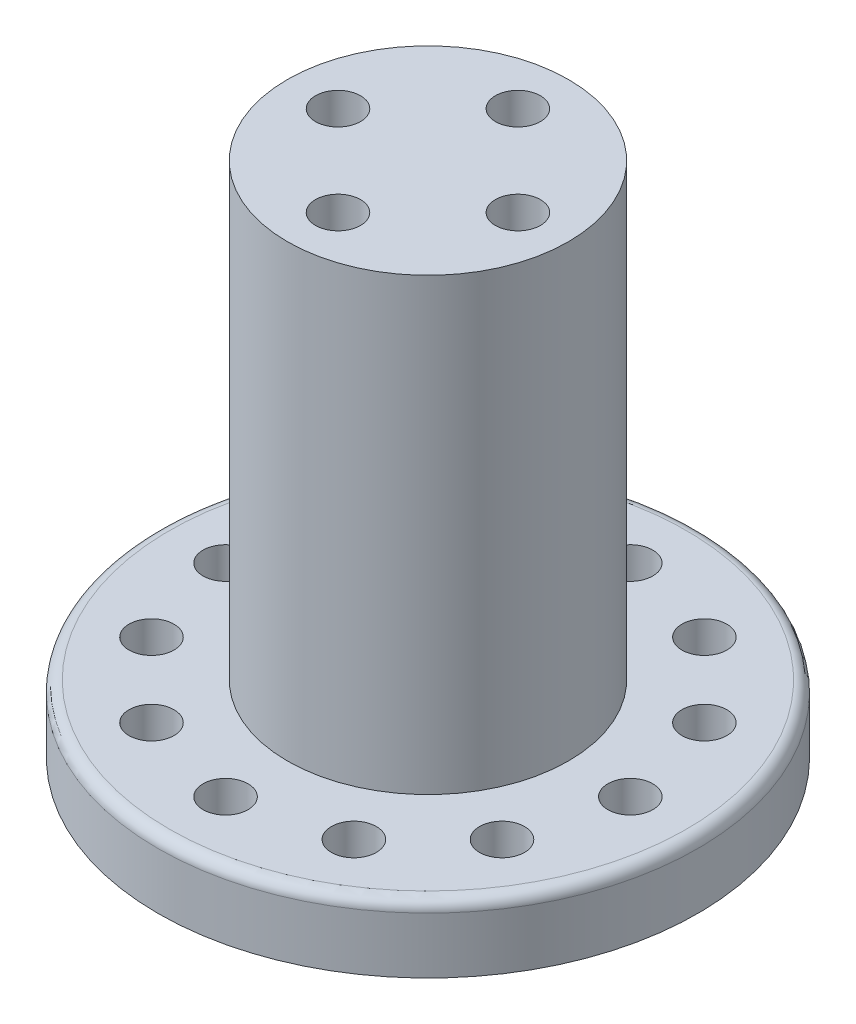
SolidWorks part; units mm, degrees
ref_plane "Front Plane" through (0, 0, 0) normal (0, 0, 1) x (1, 0, 0)
ref_plane "Top Plane" through (0, 0, 0) normal (0, 1, 0) x (1, 0, 0)
ref_plane "Right Plane" through (0, 0, 0) normal (1, 0, 0) x (0, 0, -1)
sketch "Sketch1" plane through (0, 0, 0) normal (0, 1, 0) x (1, 0, 0)
  line L0 (0, 0) -> (-22595.0444, 0) construction
  line L1 (0, 0) -> (0, -22595.0444) construction
  circle A0 centre (0, 0) radius 24
  dimension "D1" = 48
extrude "Boss-Extrude1" add sketch "Sketch1" along normal blind 6
sketch "Sketch2" plane through (0, 6, 0) normal (0, 1, 0) x (1, 0, 0)
  line L0 (0, 0) -> (-50000, 0) construction
  line L1 (0, 0) -> (0, -50000) construction
  circle A0 centre (0, 0) radius 18 construction
  circle A1 centre (0, 18) radius 2
  circle A2 centre (9, 15.5885) radius 2
  circle A3 centre (15.5885, 9) radius 2
  circle A4 centre (18, 0) radius 2
  circle A5 centre (15.5885, -9) radius 2
  circle A6 centre (9, -15.5885) radius 2
  circle A7 centre (0, -18) radius 2
  circle A8 centre (-9, -15.5885) radius 2
  circle A9 centre (-15.5885, -9) radius 2
  circle A10 centre (-18, 0) radius 2
  circle A11 centre (-15.5885, 9) radius 2
  circle A12 centre (-9, 15.5885) radius 2
  point P34 (0, 0)
  dimension "D1" = 36
  dimension "D2" = 4
  dimension "D3" = 12
extrude "Cut-Extrude1" cut sketch "Sketch2" against normal blind 4
sketch "Sketch3" plane through (0, 2, 0) normal (0, 1, 0) x (1, 0, 0)
  line L0 (0, 0) -> (-50000, 0) construction
  line L1 (0, 0) -> (0, -50000) construction
  circle A0 centre (0, 0) radius 18 construction
  circle A1 centre (0, 18) radius 1.25
  circle A2 centre (9, 15.5885) radius 1.25
  circle A3 centre (15.5885, 9) radius 1.25
  circle A4 centre (18, 0) radius 1.25
  circle A5 centre (15.5885, -9) radius 1.25
  circle A6 centre (9, -15.5885) radius 1.25
  circle A7 centre (0, -18) radius 1.25
  circle A8 centre (-9, -15.5885) radius 1.25
  circle A9 centre (-15.5885, -9) radius 1.25
  circle A10 centre (-18, 0) radius 1.25
  circle A11 centre (-15.5885, 9) radius 1.25
  circle A12 centre (-9, 15.5885) radius 1.25
  point P34 (0, 0)
  dimension "D1" = 36
  dimension "D2" = 2.5
  dimension "D3" = 12
extrude "Cut-Extrude2" cut sketch "Sketch3" against normal through all
sketch "Sketch4" plane through (0, 6, 0) normal (0, 1, 0) x (1, 0, 0)
  line L0 (0, 0) -> (-50000, 0) construction
  line L1 (0, 0) -> (0, -50000) construction
  circle A0 centre (0, 0) radius 12.5
  dimension "D1" = 25
extrude "Boss-Extrude2" add sketch "Sketch4" along normal blind 40
sketch "Sketch5" plane through (0, 0, 0) normal (0, -1, 0) x (1, 0, 0)
  line L0 (0, 0) -> (-50000, 0) construction
  line L1 (0, 0) -> (0, -50000) construction
  circle A0 centre (0, 0) radius 8.5
  dimension "D1" = 17
extrude "Cut-Extrude3" cut sketch "Sketch5" against normal blind 5
fillet "Fillet1" radius 1 1 edges at (0, 6, 24)
sketch "Sketch6" plane through (0, 46, 0) normal (0, 1, 0) x (1, 0, 0)
  line L0 (0, 0) -> (-50000, 0) construction
  line L1 (0, 0) -> (0, -50000) construction
  circle A0 centre (0, 0) radius 8 construction
  circle A2 centre (0, 8) radius 2
  circle A3 centre (8, 0) radius 2
  circle A4 centre (0, -8) radius 2
  circle A5 centre (-8, 0) radius 2
  point P19 (0, 0)
  dimension "D1" = 16
  dimension "D2" = 4
  dimension "D3" = 4
extrude "Cut-Extrude4" cut sketch "Sketch6" against normal blind 20
